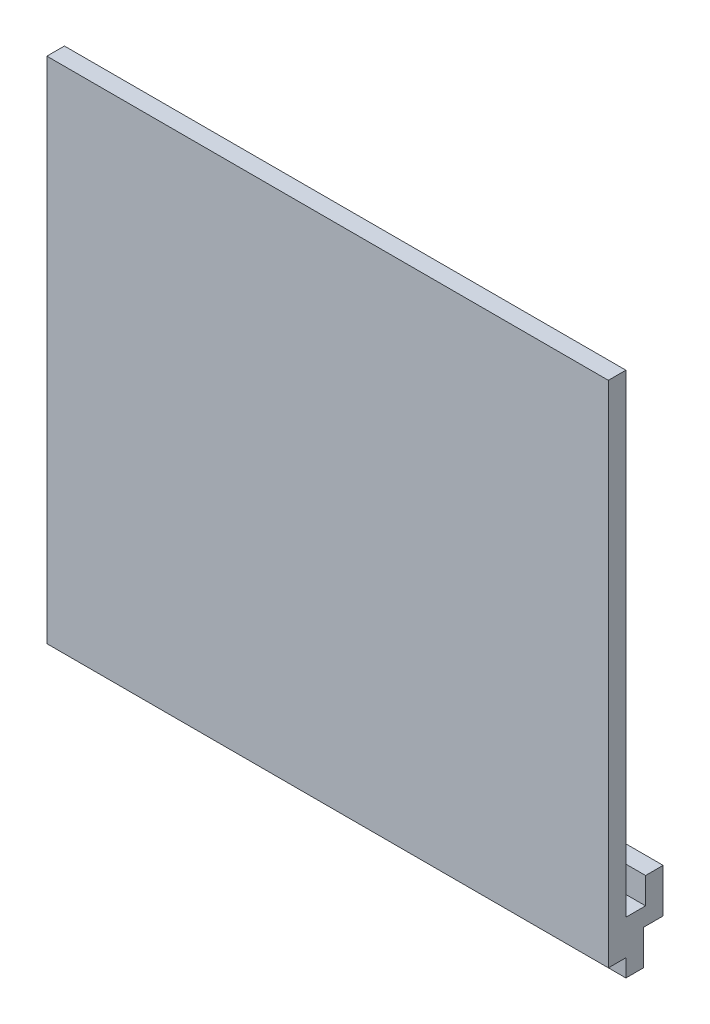
SolidWorks part; units mm, degrees
ref_plane "Front Plane" through (0, 0, 0) normal (0, 0, 1) x (1, 0, 0)
ref_plane "Top Plane" through (0, 0, 0) normal (0, 1, 0) x (1, 0, 0)
ref_plane "Right Plane" through (0, 0, 0) normal (1, 0, 0) x (0, 0, -1)
sketch "Sketch2" plane through (0, 0, 0) normal (1, 0, 0) x (0, 0, -1)
  line L0 (0, 0) -> (39.6394, 0)
  line L1 (39.6394, 0) -> (39.6394, 31.75)
  line L2 (39.6394, 31.75) -> (26.9394, 31.75)
  line L3 (26.9394, 31.75) -> (26.9394, 12.7)
  line L4 (26.9394, 12.7) -> (12.7, 12.7)
  line L5 (12.7, 12.7) -> (12.7, 355.6)
  line L6 (12.7, 355.6) -> (0, 355.6)
  line L7 (0, 355.6) -> (0, 0)
  dimension "D1" = 12.7
  dimension "D2" = 19.05
  dimension "D3" = 12.7
  dimension "D4" = 355.6
extrude "Boss-Extrude1" add sketch "Sketch2" along normal blind 406.4
sketch "Sketch3" plane through (406.4, 0, 0) normal (1, 0, 0) x (0, 0, -1)
  line L0 (12.7, 12.7) -> (12.7, 355.6) construction
  line L1 (0, 0) -> (12.7, 0)
  line L2 (0, 0) -> (0, -12.7)
  line L3 (0, -12.7) -> (12.7, -12.7)
  line L4 (12.7, 0) -> (12.7, -12.7)
  dimension "D1" = 12.7
extrude "Boss-Extrude2" add sketch "Sketch3" against normal up to surface (406.4 mm away) up to face at (0, 100.0125, -19.8197)
sketch "Sketch4" plane through (406.4, 0, 0) normal (1, 0, 0) x (0, 0, -1)
  line L0 (12.7, 12.7) -> (12.7, 355.6) construction
  line L1 (12.7, -25.4) -> (25.4, -25.4)
  line L2 (12.7, -25.4) -> (12.7, 0)
  line L3 (12.7, 0) -> (25.4, 0)
  line L4 (25.4, -25.4) -> (25.4, 0)
  line L6 (0, -12.7) -> (12.7, -12.7) construction
  dimension "D1" = 12.7
  dimension "D2" = 12.7
  dimension "D3" = 12.7
extrude "Boss-Extrude3" add sketch "Sketch4" against normal up to surface (406.4 mm away) up to face at (0, 78.105, -17.0488)
